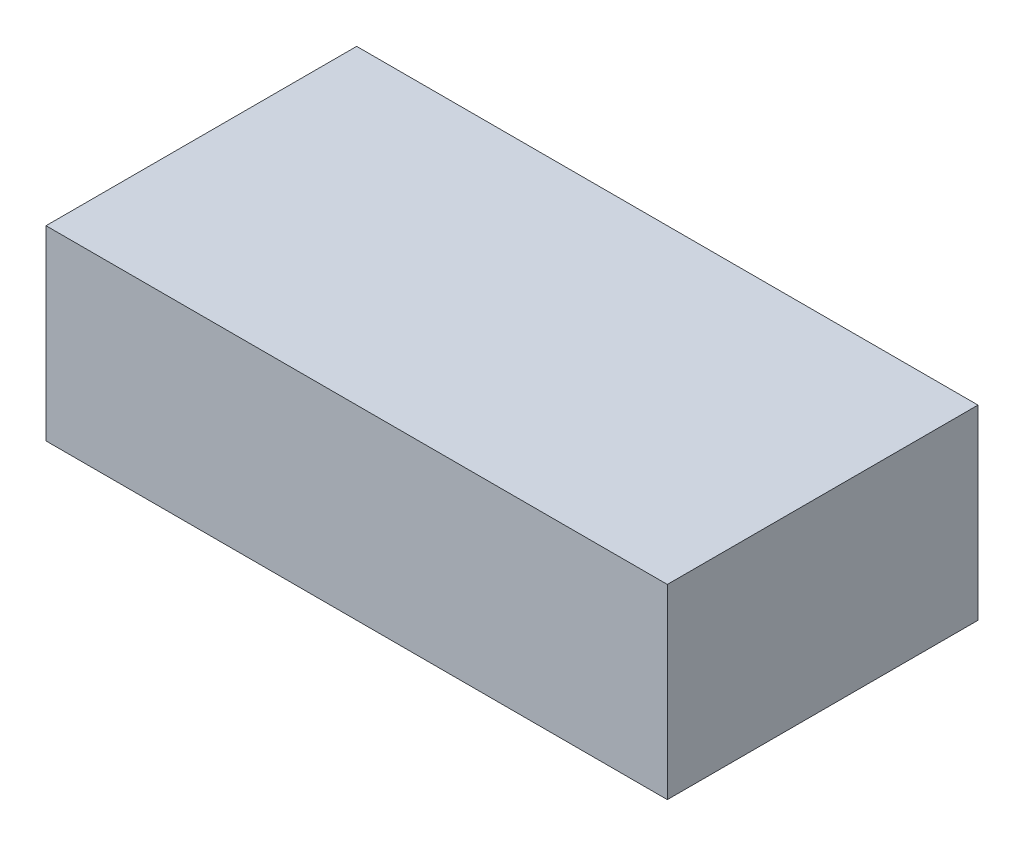
SolidWorks part; units mm, degrees
ref_plane "Front Plane" through (0, 0, 0) normal (0, 0, 1) x (1, 0, 0)
ref_plane "Top Plane" through (0, 0, 0) normal (0, 1, 0) x (1, 0, 0)
ref_plane "Right Plane" through (0, 0, 0) normal (1, 0, 0) x (0, 0, -1)
sketch "Sketch1" plane through (0, 0, 0) normal (0, 1, 0) x (1, 0, 0)
  line L1 (-10, 5) -> (10, 5)
  line L2 (-10, 5) -> (-10, -5)
  line L3 (-10, -5) -> (10, -5)
  line L4 (10, 5) -> (10, -5)
  line L5 (-10, 5) -> (10, -5) construction
  line L6 (-10, -5) -> (10, 5) construction
  point P0 (0, 0)
  dimension "D1" = 20
  dimension "D2" = 10
extrude "Boss-Extrude1" add sketch "Sketch1" along normal blind 6
